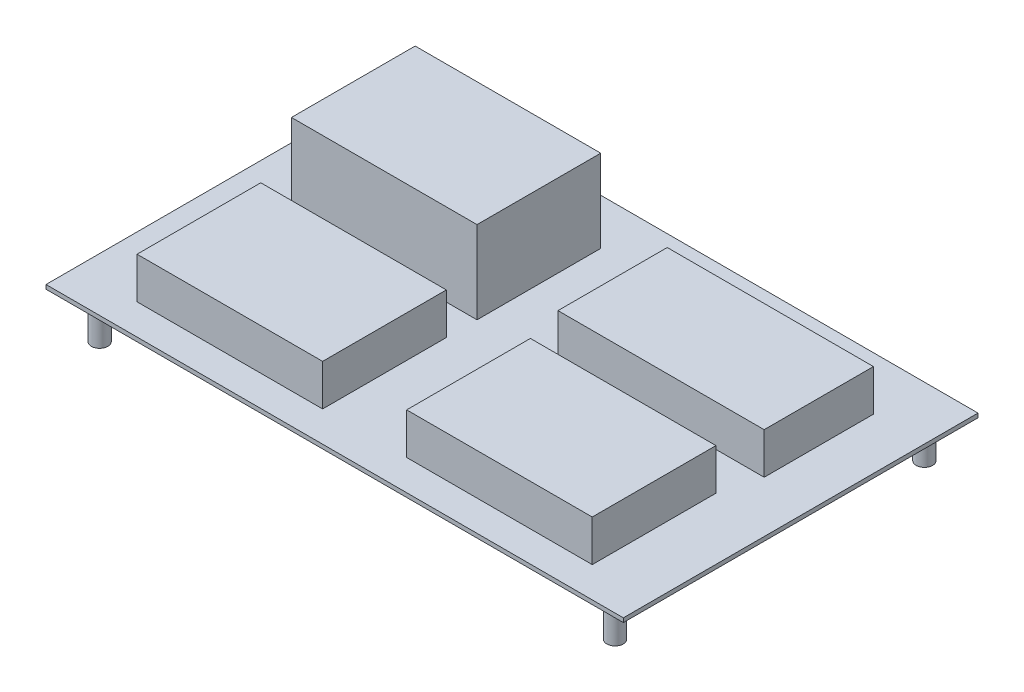
SolidWorks part; units mm, degrees
ref_plane "Спереди" through (0, 0, 0) normal (0, 0, 1) x (1, 0, 0)
ref_plane "Сверху" through (0, 0, 0) normal (0, 1, 0) x (1, 0, 0)
ref_plane "Справа" through (0, 0, 0) normal (1, 0, 0) x (0, 0, -1)
other "Configuration Table"
sketch "Эскиз1" plane through (0, 0, 0) normal (0, 1, 0) x (1, 0, 0)
  line L1 (-140, -86) -> (140, -86)
  line L2 (-140, -86) -> (-140, 86)
  line L3 (-140, 86) -> (140, 86)
  line L4 (140, -86) -> (140, 86)
  line L5 (-140, -86) -> (140, 86) construction
  line L6 (-140, 86) -> (140, -86) construction
  point P0 (0, 0)
  dimension "D1" = 280
  dimension "D2" = 172
extrude "Бобышка-Вытянуть1" add sketch "Эскиз1" along normal blind 2 contours L3 L4 L1 L2
sketch "Эскиз2" plane through (0, 2, 0) normal (0, 1, 0) x (1, 0, 0)
  line L1 (-110.6399, 3.6756) -> (-20.6399, 3.6756)
  line L2 (-110.6399, 3.6756) -> (-110.6399, 63.6756)
  line L3 (-110.6399, 63.6756) -> (-20.6399, 63.6756)
  line L4 (-20.6399, 3.6756) -> (-20.6399, 63.6756)
  line L5 (-110.6399, 3.6756) -> (-20.6399, 63.6756) construction
  line L6 (-110.6399, 63.6756) -> (-20.6399, 3.6756) construction
  line L7 (-110.6399, -71.2018) -> (-20.6399, -71.2018)
  line L8 (-110.6399, -71.2018) -> (-110.6399, -11.2018)
  line L9 (-110.6399, -11.2018) -> (-20.6399, -11.2018)
  line L10 (-20.6399, -71.2018) -> (-20.6399, -11.2018)
  line L11 (-110.6399, -71.2018) -> (-20.6399, -11.2018) construction
  line L12 (-110.6399, -11.2018) -> (-20.6399, -71.2018) construction
  line L13 (20.1162, -71.2018) -> (110.1162, -71.2018)
  line L14 (20.1162, -71.2018) -> (20.1162, -11.2018)
  line L15 (20.1162, -11.2018) -> (110.1162, -11.2018)
  line L16 (110.1162, -71.2018) -> (110.1162, -11.2018)
  line L17 (20.1162, -71.2018) -> (110.1162, -11.2018) construction
  line L18 (20.1162, -11.2018) -> (110.1162, -71.2018) construction
  line L19 (15.1162, 7.1756) -> (115.1162, 7.1756)
  line L20 (15.1162, 7.1756) -> (15.1162, 60.1756)
  line L21 (15.1162, 60.1756) -> (115.1162, 60.1756)
  line L22 (115.1162, 7.1756) -> (115.1162, 60.1756)
  line L23 (15.1162, 7.1756) -> (115.1162, 60.1756) construction
  line L24 (15.1162, 60.1756) -> (115.1162, 7.1756) construction
  point P0 (-65.6399, 33.6756)
  point P5 (-65.6399, -41.2018)
  point P10 (65.1162, -41.2018)
  point P15 (65.1162, 33.6756)
  point P16 (65.1162, 33.6756)
  point P17 (65.1162, 33.6756)
  dimension "D1" = 90
  dimension "D2" = 60
  dimension "D3" = 53
  dimension "D4" = 100
extrude "Бобышка-Вытянуть2" add sketch "Эскиз2" along normal blind 20
sketch "Эскиз3" plane through (0, 22, 0) normal (0, 1, 0) x (1, 0, 0)
  line L1 (-110.6399, 63.6756) -> (-20.6399, 63.6756)
  line L2 (-110.6399, 63.6756) -> (-110.6399, 3.6756)
  line L3 (-110.6399, 3.6756) -> (-20.6399, 3.6756)
  line L4 (-20.6399, 63.6756) -> (-20.6399, 3.6756)
extrude "Бобышка-Вытянуть3" add sketch "Эскиз3" along normal blind 20
sketch "Эскиз4" plane through (0, 0, 0) normal (0, -1, 0) x (1, 0, 0)
  line L1 (125, -75) -> (-125, -75) construction
  line L2 (125, -75) -> (125, 75) construction
  line L3 (125, 75) -> (-125, 75) construction
  line L4 (-125, -75) -> (-125, 75) construction
  line L5 (125, -75) -> (-125, 75) construction
  line L6 (125, 75) -> (-125, -75) construction
  circle A0 centre (-125, 75) radius 4
  circle A1 centre (125, 75) radius 4
  circle A2 centre (125, -75) radius 4
  circle A3 centre (-125, -75) radius 4
  point P2 (0, 0)
  dimension "D3" = 8
  dimension "D1" = 250
  dimension "D2" = 150
  dimension "D4" = 2
  dimension "D5" = 2
extrude "Бобышка-Вытянуть4" add sketch "Эскиз4" along normal blind 20
